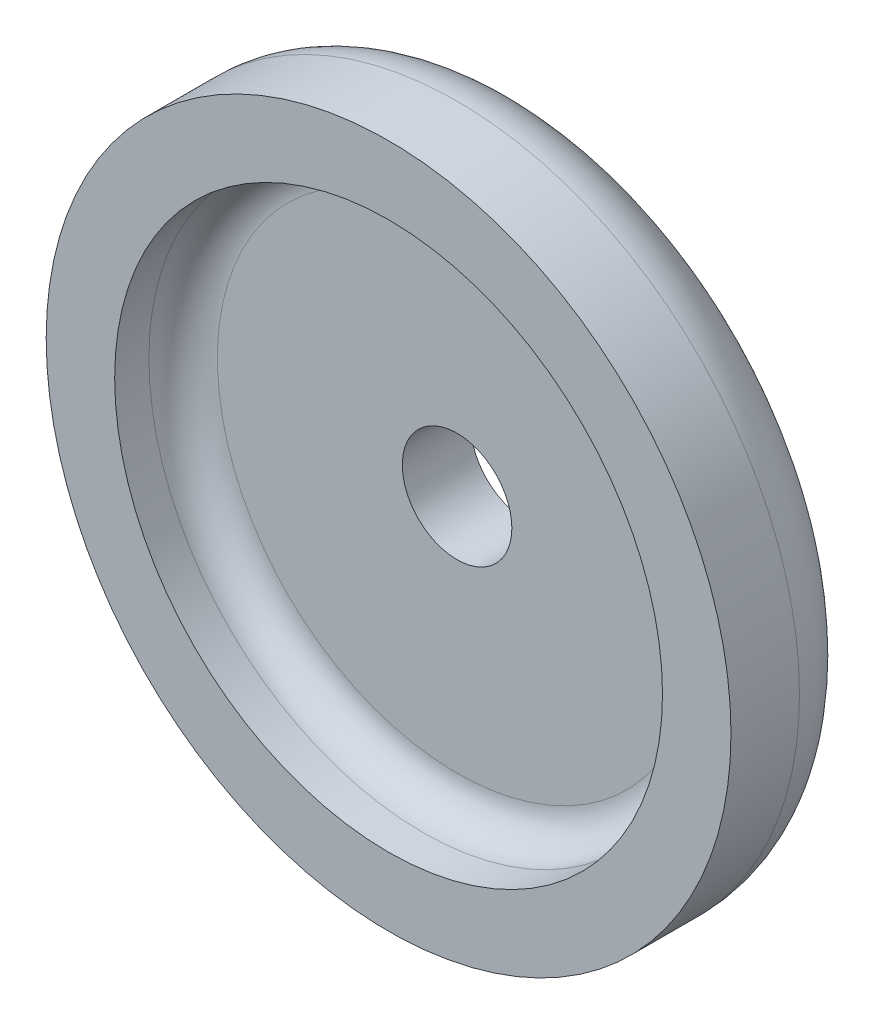
SolidWorks part; units mm, degrees
ref_plane "前视基准面" through (0, 0, 0) normal (0, 0, 1) x (1, 0, 0)
ref_plane "上视基准面" through (0, 0, 0) normal (0, 1, 0) x (1, 0, 0)
ref_plane "右视基准面" through (0, 0, 0) normal (1, 0, 0) x (0, 0, -1)
sketch "草图1" plane through (0, 0, 0) normal (0, 0, 1) x (1, 0, 0)
  circle A0 centre (0, 0) radius 5
  dimension "D1" = 10
extrude "凸台-拉伸1" add sketch "草图1" along normal blind 2
shell "抽壳1" thickness 1
fillet "圆角1" radius 0.5 1 edges at (4, 0, 1)
fillet "圆角2" radius 1 1 edges at (5, 0, 0)
hole_wizard "M2 螺纹孔1" positions "草图2" profile "草图3" tap size "M2" standard "GB"
sketch "草图2" plane through (0, 0, 1) normal (0, 0, 1) x (1, 0, 0)
  point P0 (0, 0)
sketch "草图3" plane through (0, 0, 1) normal (1, 0, 0) x (0, -1, 0)
  line L0 (0, 0) -> (0, 5.6807)
  line L1 (0, 5.6807) -> (0.8, 5.2)
  line L2 (0.8, 5.2) -> (0.8, 0)
  line L5 (0.8, 0) -> (0, 0)
  line L10 (0, 5.6807) -> (-0.8, 5.2) construction
  line L11 (0, -6.35) -> (0, 107.95) construction
  dimension "螺纹孔钻头直径" = 1.6
  dimension "螺纹孔钻头深度" = 5.2
  dimension "导头角度" = 118
cosmetic thread "孔螺纹线1" parameters "D1"=4, "D2"=2
